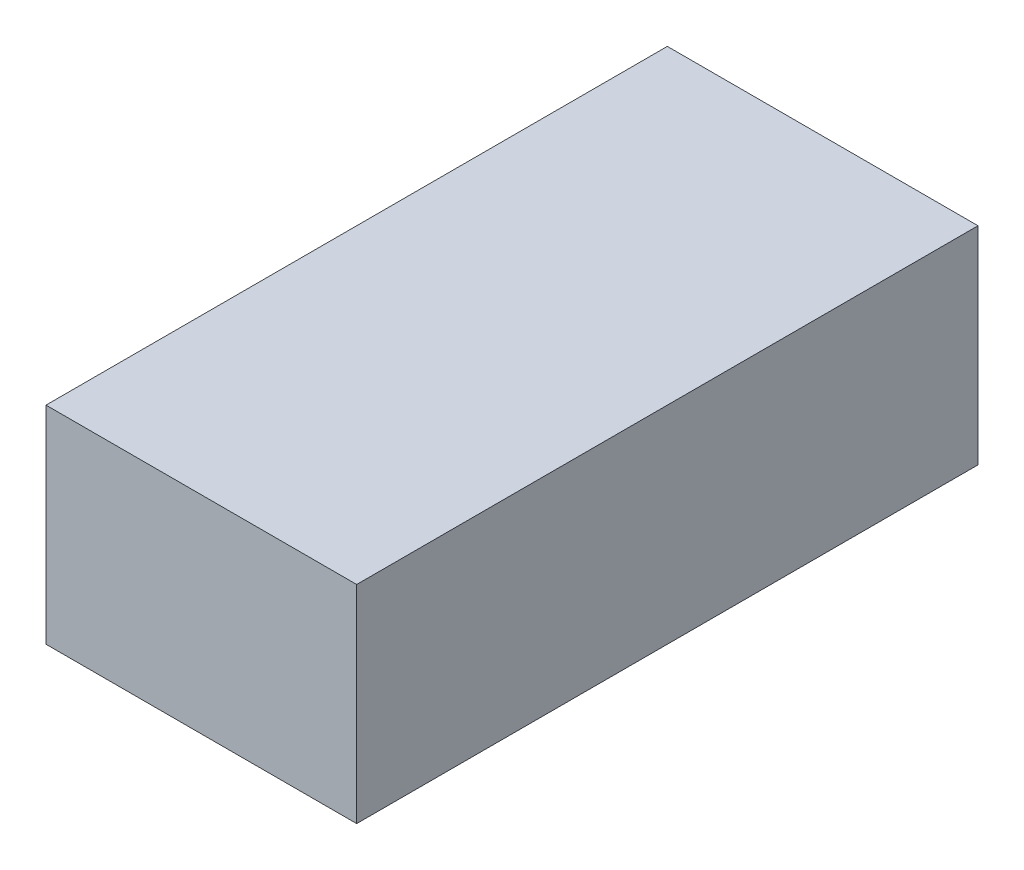
SolidWorks part; units mm, degrees
ref_plane "Plan de face" through (0, 0, 0) normal (0, 0, 1) x (1, 0, 0)
ref_plane "Plan de dessus" through (0, 0, 0) normal (0, 1, 0) x (1, 0, 0)
ref_plane "Plan de droite" through (0, 0, 0) normal (1, 0, 0) x (0, 0, -1)
sketch "Esquisse1" plane through (0, 0, 0) normal (0, 1, 0) x (1, 0, 0)
  line L1 (-65.7209, -88.3256) -> (24.2791, -88.3256)
  line L2 (-65.7209, -88.3256) -> (-65.7209, 91.6744)
  line L3 (-65.7209, 91.6744) -> (24.2791, 91.6744)
  line L4 (24.2791, -88.3256) -> (24.2791, 91.6744)
  dimension "D1" = 180
  dimension "D2" = 90
extrude "Boss.-Extru.1" add sketch "Esquisse1" along normal blind 60
sketch "Esquisse2" plane through (0, 60, 0) normal (0, 1, 0) x (1, 0, 0)
  line L0 (24.2791, 91.6744) -> (-65.7209, 91.6744) construction
  line L1 (-8.8723, 91.6744) -> (-38.8723, 91.6744)
  line L2 (-8.8723, 91.6744) -> (-8.8723, -88.3256)
  line L3 (-8.8723, -88.3256) -> (-38.8723, -88.3256)
  line L4 (-38.8723, 91.6744) -> (-38.8723, -88.3256)
  line L5 (-65.7209, -88.3256) -> (24.2791, -88.3256) construction
  line L6 (24.2791, -88.3256) -> (-25.7209, -88.3256)
  dimension "D1" = 30
  dimension "D2" = 50
